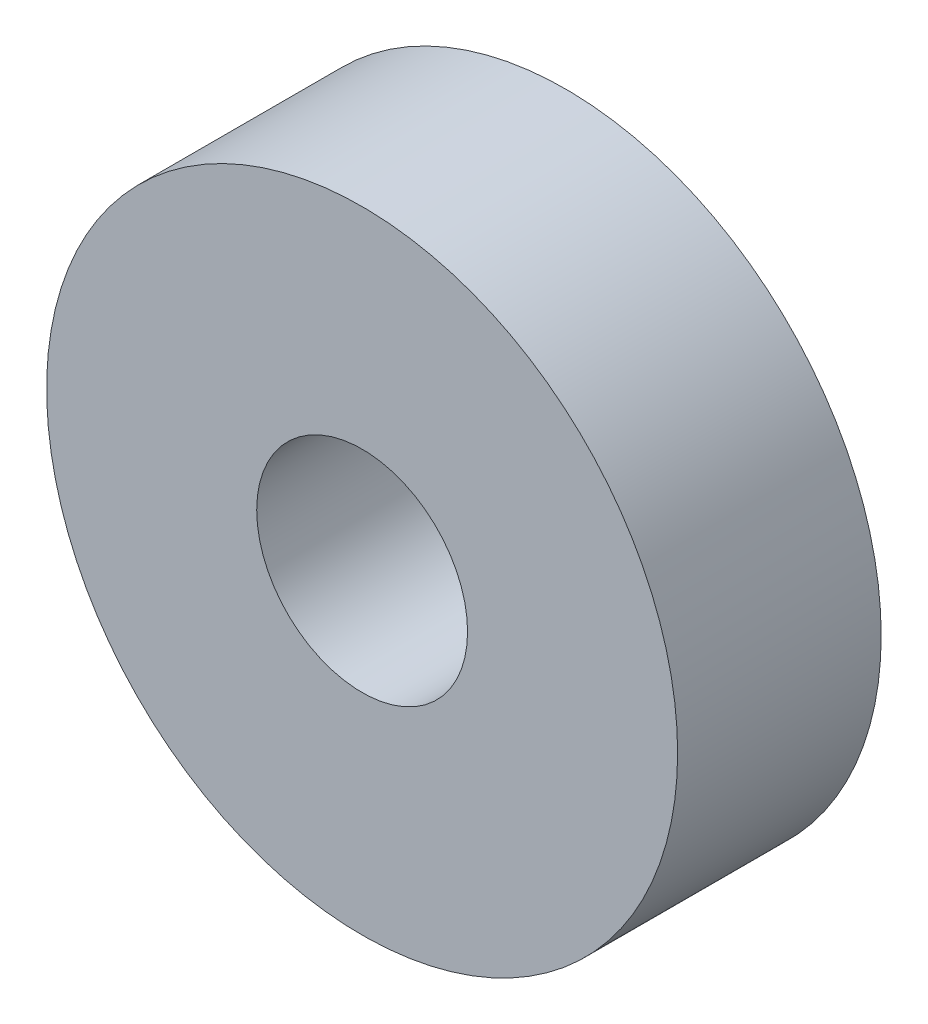
SolidWorks part; units mm, degrees
ref_plane "Front Plane" through (0, 0, 0) normal (0, 0, 1) x (1, 0, 0)
ref_plane "Top Plane" through (0, 0, 0) normal (0, 1, 0) x (1, 0, 0)
ref_plane "Right Plane" through (0, 0, 0) normal (1, 0, 0) x (0, 0, -1)
sketch "Sketch1" plane through (0, 0, 0) normal (0, 0, 1) x (1, 0, 0)
  circle A0 centre (0, 0) radius 7.75
  circle A1 centre (0, 0) radius 2.59
  dimension "D1" = 5.18
  dimension "D2" = 15.5
extrude "Boss-Extrude1" add sketch "Sketch1" along normal blind 5
sketch "Sketch2" plane through (0, 0, 0) normal (0, 0, -1) x (-1, 0, 0)
  circle A0 centre (0, 0) radius 3.5
  circle A1 centre (0, 0) radius 6.5
  dimension "D1" = 7
  dimension "D2" = 13
extrude "Cut-Extrude1" cut sketch "Sketch2" against normal blind 2
sketch "Sketch5" plane through (0, 0, 0) normal (0, 0, -1) x (-1, 0, 0)
  circle A0 centre (0, 0) radius 4.4664
  circle A1 centre (0, 0) radius 10.3902
